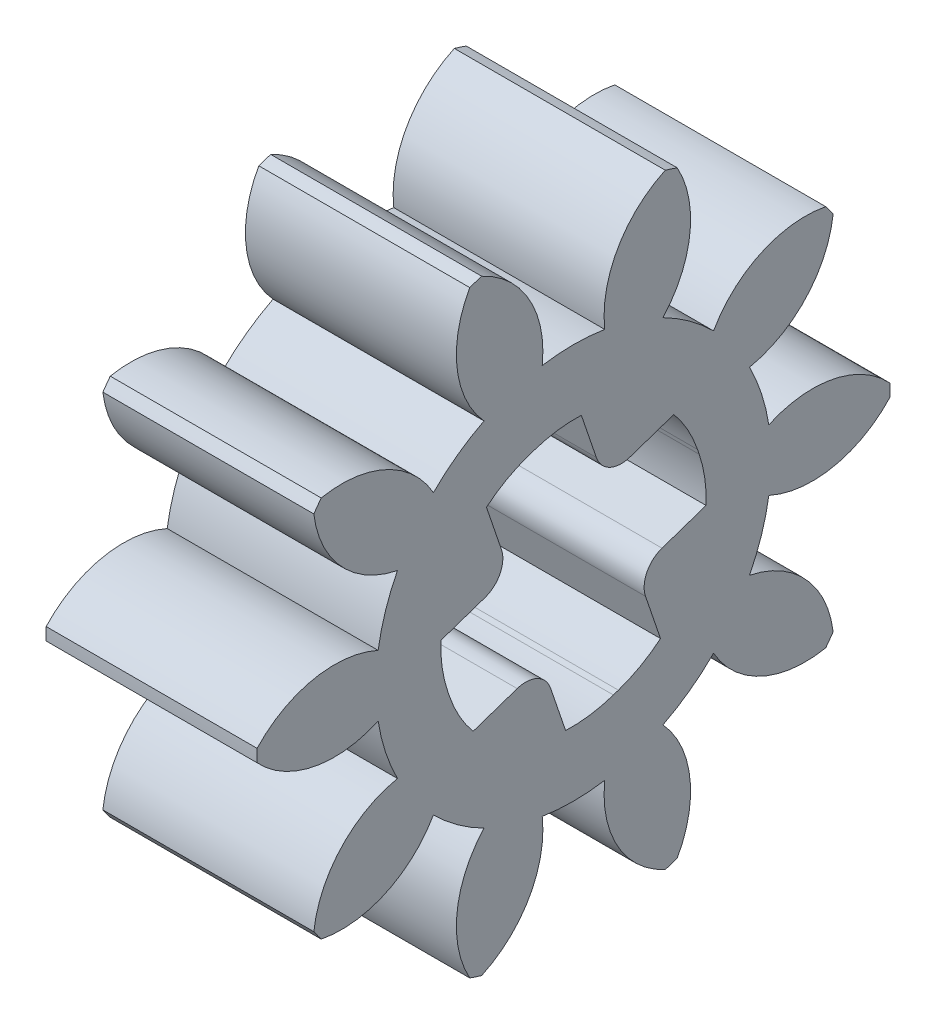
SolidWorks part; units mm, degrees
ref_plane "Plane1" through (0, 0, 0) normal (0, 0, 1) x (1, 0, 0)
ref_plane "Plane2" through (0, 0, 0) normal (0, 1, 0) x (1, 0, 0)
ref_plane "Plane3" through (0, 0, 0) normal (1, 0, 0) x (0, 0, -1)
sketch "HoldingSke" plane through (0, 0, 0) normal (0, 1, 0) x (1, 0, 0)
  line L0 (0, 0) -> (0.9848, -0.1736)
  line L1 (-15, 0) -> (100, 0) construction
  line L2 (0, 0) -> (-2.1039, 2.3779)
  line L3 (0, 0) -> (-11.863, 4.5341)
  line L4 (0, 0) -> (8.5048, 1.4996)
  line L5 (0, 0) -> (-46.8476, -17.4728)
  line L6 (0, 0) -> (-3.3159, -2.2372)
  line L7 (-2.1039, 2.3779) -> (8.6586, 51.2059)
  line L8 (-76.2, 54.61) -> (-75.3, 54.61)
  line L9 (-71.009, 38.7566) -> (-53.1078, 45.2721)
  line L10 (-76.2, 71.12) -> (104.1128, 71.12)
  line L11 (0, 0) -> (-4, 0)
  line L12 (-76.2, 101.6) -> (-76.162, 101.6)
  line L13 (24.9733, 27.94) -> (52.9518, 28.4284)
  line L14 (24.9733, 27.94) -> (24.9743, 27.94)
  line L15 (24.9733, 27.94) -> (100.4006, 29.5858)
  line L16 (-63.627, -1) -> (-12.827, -1)
  circle A0 centre (0, 0) radius 2.5
  circle A1 centre (0, 0) radius 3.749
  circle A2 centre (0, 0) radius 37.5
  circle A3 centre (0, 0) radius 2.5
  dimension "MHD" = 7.498
  dimension "Hub_dia" = 75
  dimension "Bore" = 5
  dimension "MBD" = 5
  dimension "Num_teeth" = 10
  dimension "Pitch" = 1
  dimension "Overall_len" = 50
  dimension "Show_teeth" = 10
  dimension "Thickness" = 4
  dimension "OAL" = 50.0001
  dimension "T_dim" = 0.9
  dimension "Ap" = 20
  dimension "H" = 19.05
  dimension "Pitch_radius" = 180.3128
  dimension "Width" = 4
  dimension "Backlash" = 0.038
  dimension "Addendum_fac" = 1
  dimension "Dedendum_fac" = 1.25
  dimension "Clearance_fac" = 0.25
  dimension "Dedendum_add" = 0.001
  dimension "Module" = 1
sketch "BasProSke" plane through (0, 0, 0) normal (0, 1, 0) x (1, 0, 0)
  line L0 (-10, 0) -> (60, 0) construction
  line L1 (0, 0) -> (0, 6)
  line L2 (0, 0) -> (4, 0)
  line L3 (4, 0) -> (4, 6)
  line L4 (4, 6) -> (0, 6)
  dimension "Thickness" = 4
  dimension "Diameter" = 12
revolve "Base-Revolve" add sketch "BasProSke" angle 360 about L0
sketch "TooCutSke" plane through (0, 0, 0) normal (1, 0, 0) x (0, 0, -1)
  line L1 (0, 0) -> (0, 107) construction
  line L2 (0, 0) -> (-0.8485, 4.9275) construction
  line L3 (0, 0) -> (-3.0584, 9.4126) construction
  line L4 (-0.8485, 4.9275) -> (-1.5292, 4.7063) construction
  arc A0 (0.5928, 3.7018) -> (-0.5928, 3.7018) centre (0, 0) ccw
  arc A1 (1.7758, 5.7578) -> (-1.7758, 5.7578) centre (0, 0) ccw
  circle A2 centre (0, 0) radius 5 construction
  circle A3 centre (0, 0) radius 4.6985 construction
  arc A4 (-0.5928, 3.7018) -> (-1.7758, 5.7578) centre (-2.5801, 3.9267) ccw
  arc A5 (1.7758, 5.7578) -> (0.5928, 3.7018) centre (2.5801, 3.9267) ccw
  dimension "Root_dia" = 7.498
  dimension "Overcut_dia" = 12.0508
  dimension "Pitch_dia" = 10
  dimension "Base_dia" = 9.3969
  dimension "Flank_rad" = 2
  dimension "Half_ang" = 18
  dimension "Half_CT" = 0.7157
extrude "ToothCut" cut sketch "TooCutSke" along normal through all
fillet "Breaks" [suppressed] radius 0.02
fillet "RootFillets" [suppressed] radius 0.251
pattern_circular "TeethCuts" count 10 every 36 about axis through (-10, 0, 0) along (1, 0, 0) of "ToothCut", "RootFillets", "Breaks"
sketch "HubNeaOneSke" plane through (0, 0, 0) normal (-1, 0, 0) x (0, 0, 1)
  circle A0 centre (0, 0) radius 3.749
  dimension "Diameter" = 7.498
extrude "HubNearOne" [suppressed] add sketch "HubNeaOneSke" along normal blind 46.0001
sketch "HubNeaBotSke" plane through (0, 0, 0) normal (-1, 0, 0) x (0, 0, 1)
  circle A0 centre (0, 0) radius 3.749
  dimension "Diameter" = 7.498
extrude "HubNearBoth" [suppressed] add sketch "HubNeaBotSke" along normal blind 23
ref_plane "FarPln" through (4, 0, 0) normal (1, 0, 0) x (0, 0, -1)
sketch "HubFarSke" plane through (4, 0, 0) normal (1, 0, 0) x (0, 0, -1)
  circle A0 centre (0, 0) radius 3.749
  dimension "Diameter" = 7.498
extrude "HubFar" [suppressed] add sketch "HubFarSke" along normal blind 23
sketch "BorSke" plane through (0, 0, 0) normal (1, 0, 0) x (0, 0, -1)
  circle A0 centre (0, 0) radius 2.5
  dimension "Diameter" = 5
extrude "Bore" cut sketch "BorSke" along normal mid plane 100.0001
sketch "KeySke" plane through (0, 0, 0) normal (1, 0, 0) x (0, 0, -1)
  line L0 (-1, 0) -> (-1, 3.4)
  line L1 (-1, 3.4) -> (1, 3.4)
  line L2 (1, 3.4) -> (1, 0)
  line L3 (0, 0) -> (0, 34) construction
  line L4 (-1, 0) -> (1, 0)
  dimension "Offset" = 3.4
  dimension "Width" = 2
extrude "Keyway" [suppressed] cut sketch "KeySke" along normal mid plane 100.0001
pattern_circular "Keyway2" [suppressed] count 2 every 90 about axis through (-10, 0, 0) along (1, 0, 0)
sketch "Sketch2" plane through (0, 0, 0) normal (-1, 0, 0) x (0, 0, 1)
  circle A0 centre (0, 0) radius 3
  dimension "D1" = 6
extrude "Cut-Extrude1" cut sketch "Sketch2" against normal through all
sketch "Sketch1" plane through (4, 0, 0) normal (1, 0, 0) x (0, 0, -1)
  line L12 (-0.433, -1.6785) -> (-0.1492, -2.514)
  line L13 (-1.9028, -1.6498) -> (-1.0673, -1.366)
  line L14 (-2.3832, -0.7569) -> (-2.351, -0.8516)
  line L15 (-1.6785, 0.433) -> (-2.514, 0.1492)
  line L16 (-1.6498, 1.9028) -> (-1.366, 1.0673)
  line L17 (-0.7569, 2.3832) -> (-0.8516, 2.351)
  line L18 (0.433, 1.6785) -> (0.1492, 2.514)
  line L19 (1.9028, 1.6498) -> (1.0673, 1.366)
  line L20 (2.3832, 0.7569) -> (2.351, 0.8516)
  line L21 (1.6785, -0.433) -> (2.514, -0.1492)
  line L22 (1.6498, -1.9028) -> (1.366, -1.0673)
  line L23 (0.7569, -2.3832) -> (0.8516, -2.351)
  line L24 (-0.433, -1.6785) -> (-0.1492, -2.514)
  line L25 (-1.9028, -1.6498) -> (-1.0673, -1.366)
  line L26 (-2.3832, -0.7569) -> (-2.351, -0.8516)
  line L27 (-1.6785, 0.433) -> (-2.514, 0.1492)
  line L28 (-1.6498, 1.9028) -> (-1.366, 1.0673)
  line L29 (-0.7569, 2.3832) -> (-0.8516, 2.351)
  line L30 (0.433, 1.6785) -> (0.1492, 2.514)
  line L31 (1.9028, 1.6498) -> (1.0673, 1.366)
  line L32 (2.3832, 0.7569) -> (2.351, 0.8516)
  line L33 (1.6785, -0.433) -> (2.514, -0.1492)
  line L34 (1.6498, -1.9028) -> (1.366, -1.0673)
  line L35 (0.7569, -2.3832) -> (0.8516, -2.351)
  circle A1 centre (0, 0) radius 3
  circle A2 centre (0, 0) radius 3 construction
  arc A14 (-0.1492, -2.514) -> (0.7569, -2.3832) centre (-0.0473, -0.0161) ccw
  arc A15 (-0.433, -1.6785) -> (-1.0673, -1.366) centre (-0.9064, -1.8394) ccw
  arc A16 (-2.351, -0.8516) -> (-1.9028, -1.6498) centre (0.0161, -0.0473) ccw
  arc A17 (-2.514, 0.1492) -> (-2.3832, -0.7569) centre (-0.0161, 0.0473) ccw
  arc A18 (-1.6785, 0.433) -> (-1.366, 1.0673) centre (-1.8394, 0.9064) ccw
  arc A19 (-0.8516, 2.351) -> (-1.6498, 1.9028) centre (-0.0473, -0.0161) ccw
  arc A20 (0.1492, 2.514) -> (-0.7569, 2.3832) centre (0.0473, 0.0161) ccw
  arc A21 (0.433, 1.6785) -> (1.0673, 1.366) centre (0.9064, 1.8394) ccw
  arc A22 (2.351, 0.8516) -> (1.9028, 1.6498) centre (-0.0161, 0.0473) ccw
  arc A23 (2.514, -0.1492) -> (2.3832, 0.7569) centre (0.0161, -0.0473) ccw
  arc A24 (1.6785, -0.433) -> (1.366, -1.0673) centre (1.8394, -0.9064) ccw
  arc A25 (0.8516, -2.351) -> (1.6498, -1.9028) centre (0.0473, 0.0161) ccw
  arc A26 (-0.1492, -2.514) -> (0.7569, -2.3832) centre (-0.0473, -0.0161) ccw
  arc A27 (-0.433, -1.6785) -> (-1.0673, -1.366) centre (-0.9064, -1.8394) ccw
  arc A28 (-2.351, -0.8516) -> (-1.9028, -1.6498) centre (0.0161, -0.0473) ccw
  arc A29 (-2.514, 0.1492) -> (-2.3832, -0.7569) centre (-0.0161, 0.0473) ccw
  arc A30 (-1.6785, 0.433) -> (-1.366, 1.0673) centre (-1.8394, 0.9064) ccw
  arc A31 (-0.8516, 2.351) -> (-1.6498, 1.9028) centre (-0.0473, -0.0161) ccw
  arc A32 (0.1492, 2.514) -> (-0.7569, 2.3832) centre (0.0473, 0.0161) ccw
  arc A33 (0.433, 1.6785) -> (1.0673, 1.366) centre (0.9064, 1.8394) ccw
  arc A34 (2.351, 0.8516) -> (1.9028, 1.6498) centre (-0.0161, 0.0473) ccw
  arc A35 (2.514, -0.1492) -> (2.3832, 0.7569) centre (0.0161, -0.0473) ccw
  arc A36 (1.6785, -0.433) -> (1.366, -1.0673) centre (1.8394, -0.9064) ccw
  arc A37 (0.8516, -2.351) -> (1.6498, -1.9028) centre (0.0473, 0.0161) ccw
  dimension "D1" = 0
extrude "Boss-Extrude1" add sketch "Sketch1" against normal up to surface (4 mm away) up to face at (0, 0, 3)
equation "' \"Module@HoldingSke\" = 6.35"
equation "' \"Num_teeth@HoldingSke\" = 12"
equation "' \"Ap@HoldingSke\" =  20"
equation "' \"Ap@HoldingSke\" = 20"
equation "' \"Width@HoldingSke\" = 0.5 * 25.4"
equation "' \"Hub_dia@HoldingSke\"= 1 * 25.4"
equation "' \"Hub_dia@HoldingSke\" = 1 * 25.4"
equation "' \"Overall_len@HoldingSke\" = 1.0 * 25.4"
equation "' \"Bore@HoldingSke\" = 0.75 * 25.4"
equation "' \"T_dim@HoldingSke\" = 0.1 * 25.4"
equation "' \"Width@KeySke\" = 0.25 * 25.4"
equation "' \"Show_teeth@HoldingSke\" = 13"
equation "' \"Backlash@HoldingSke\" = 0.009 * 25.4"
equation "' \"Addendum_fac@HoldingSke\" = 1.0"
equation "' \"Dedendum_fac@HoldingSke\" = 1.25"
equation "' \"Dedendum_add@HoldingSke\" = 0.00005 * 25.4"
equation "' \"Clearance_fac@HoldingSke\" = 0.25"
equation "\"Pitch@HoldingSke\" = 1 / \"Module@HoldingSke\""
equation "\"Overcut_dia@TooCutSke\" = (\"Num_teeth@HoldingSke\" + 2 * \"Addendum_fac@HoldingSke\") / \"Pitch@HoldingSke\" + 0.002 * 25.4"
equation "\"Pitch_dia@TooCutSke\" = \"Num_teeth@HoldingSke\" / \"Pitch@HoldingSke\""
equation "\"Base_dia@TooCutSke\" = \"Num_teeth@HoldingSke\" / \"Pitch@HoldingSke\" * cos((\"Ap@HoldingSke\"  * 3.14159265 / 180))"
equation "\"Root_dia@TooCutSke\" = (\"Num_teeth@HoldingSke\" + 2) / \"Pitch@HoldingSke\" - 2 * (\"Addendum_fac@HoldingSke\" + \"Dedendum_fac@HoldingSke\") / \"Pitch@HoldingSke\" - \"Dedendum_add@HoldingSke\" * 2"
equation "\"Half_ang@TooCutSke\" = 180 / \"Num_teeth@HoldingSke\""
equation "\"Half_CT@TooCutSke\" = \"Num_teeth@HoldingSke\" / \"Pitch@HoldingSke\" * sin((3.14159265 / 2 / \"Num_teeth@HoldingSke\")) / 2 - 7 * \"Backlash@HoldingSke\" / 4"
equation "\"Flank_rad@TooCutSke\" = \"Num_teeth@HoldingSke\" / \"Pitch@HoldingSke\" / 5"
equation "\"Radius@RootFillets\" = \"Clearance_fac@HoldingSke\" / \"Pitch@HoldingSke\" + \"Dedendum_add@HoldingSke\""
equation "\"Break_rad@Breaks\" = 0.02 / \"Pitch@HoldingSke\""
equation "\"Thickness@HoldingSke\" = \"Width@HoldingSke\""
equation "\"OAL@HoldingSke\" = \"Thickness@HoldingSke\""
equation "\"MHD@HoldingSke\" = (\"Num_teeth@HoldingSke\" + 2) / \"Pitch@HoldingSke\" - 2 * (\"Addendum_fac@HoldingSke\" + \"Dedendum_fac@HoldingSke\")  / \"Pitch@HoldingSke\" - \"Dedendum_add@HoldingSke\" * 2"
equation "\"MBD@HoldingSke\" = (\"Num_teeth@HoldingSke\" + 2) / \"Pitch@HoldingSke\" - 2 * (\"Addendum_fac@HoldingSke\" + \"Dedendum_fac@HoldingSke\")  / \"Pitch@HoldingSke\" - \"Dedendum_add@HoldingSke\" * 2 - 0.002 * 25.4"
equation "\"MHD@HoldingSke\" = ((sgn( \"MHD@HoldingSke\" - \"Hub_dia@HoldingSke\" )-1)*( \"MHD@HoldingSke\" - \"Hub_dia@HoldingSke\" ))/-2+ \"Hub_dia@HoldingSke\""
equation "\"MBD@HoldingSke\" = ((sgn( \"MBD@HoldingSke\" - \"Bore@HoldingSke\" )-1)*( \"MBD@HoldingSke\" - \"Bore@HoldingSke\" ))/-2+ \"Bore@HoldingSke\""
equation "\"OAL@HoldingSke\" = ((sgn( \"OAL@HoldingSke\" - \"Overall_len@HoldingSke\" )+1)*( \"OAL@HoldingSke\" - \"Overall_len@HoldingSke\" ))/2 + \"Overall_len@HoldingSke\" + 0.000002 * 25.4"
equation "\"Num_teeth@TeethCuts\" = int( \"Show_teeth@HoldingSke\" ) + 1"
equation "\"Num_teeth@TeethCuts\" = ((sgn( \"Num_teeth@TeethCuts\" - \"Num_teeth@HoldingSke\" )-1)*( \"Num_teeth@TeethCuts\" - \"Num_teeth@HoldingSke\" ))/-2+ \"Num_teeth@HoldingSke\""
equation "\"Num_teeth@TeethCuts\" = ((sgn( \"Num_teeth@TeethCuts\" - 2.0)+1)*( \"Num_teeth@TeethCuts\" - 2.0))/2 +2.0"
equation "\"Angle@TeethCuts\" = 360.0 / \"Num_teeth@HoldingSke\""
equation "\"Diameter@BasProSke\" = (\"Num_teeth@HoldingSke\" + 2 * \"Addendum_fac@HoldingSke\") / \"Pitch@HoldingSke\""
equation "\"Thickness@BasProSke\"  = \"Thickness@HoldingSke\""
equation "' \"Fillet_rad@BasProSke\" =  \"Thickness@HoldingSke\" * 0.05"
equation "' \"Fillet_rad@BasProSke\" = \"Thickness@HoldingSke\" * 0.05"
equation "\"MHD@HoldingSke\" = ((sgn( \"MHD@HoldingSke\" - \"Root_dia@TooCutSke\" )-1)*( \"MHD@HoldingSke\" - \"Root_dia@TooCutSke\" ))/-2+ \"Root_dia@TooCutSke\""
equation "\"Diameter@HubNeaOneSke\" = \"MHD@HoldingSke\""
equation "\"Length@HubNearOne\" = \"OAL@HoldingSke\" - \"Thickness@BasProSke\""
equation "\"Diameter@HubNeaBotSke\" = \"MHD@HoldingSke\""
equation "\"Length@HubNearBoth\" = ( \"OAL@HoldingSke\" - \"Thickness@BasProSke\" ) / 2.0"
equation "\"Thickness@FarPln\" = \"Thickness@BasProSke\""
equation "\"Diameter@HubFarSke\" = \"MHD@HoldingSke\""
equation "\"Length@HubFar\" = ( \"OAL@HoldingSke\" - \"Thickness@BasProSke\" ) / 2.0"
equation "\"Diameter@BorSke\" = \"MBD@HoldingSke\""
equation "\"D1@Bore\" = \"OAL@HoldingSke\" * 2.0"
equation "\"D1@Keyway\" = \"OAL@HoldingSke\" * 2.0"
equation "\"Offset@KeySke\" = \"T_dim@HoldingSke\" + \"MBD@HoldingSke\" / 2.0"
